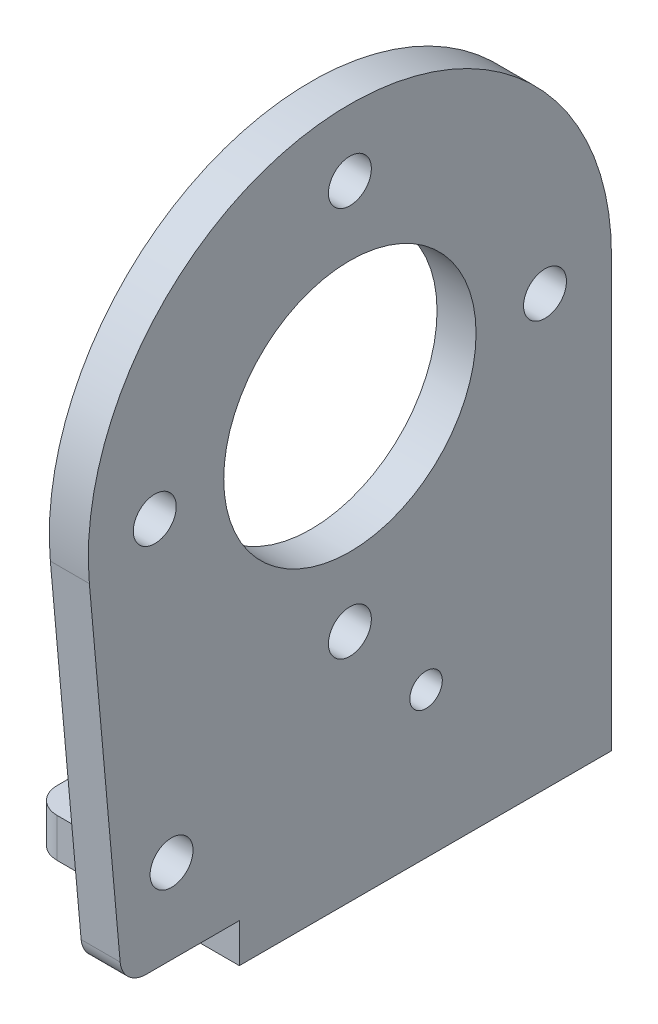
SolidWorks part; units mm, degrees
ref_plane "前视基准面" through (0, 0, 0) normal (0, 0, 1) x (1, 0, 0)
ref_plane "上视基准面" through (0, 0, 0) normal (0, 1, 0) x (1, 0, 0)
ref_plane "右视基准面" through (0, 0, 0) normal (1, 0, 0) x (0, 0, -1)
sketch "草图2" plane through (0, 0, 0) normal (1, 0, 0) x (0, 0, -1)
  line L0 (9, 13) -> (61, 13)
  line L1 (37.6103, 13) -> (37.6103, 10)
  line L2 (9, 10) -> (61, 10)
  line L5 (9, 10) -> (9, 16)
  line L6 (9, 16) -> (61, 16)
  line L7 (61, 10) -> (61, 16)
extrude "凸台-拉伸5" add sketch "草图2" against normal blind 16 contours L5 L2 L1 L0
sketch "草图5" plane through (0, 0, 0) normal (1, 0, 0) x (0, 0, -1)
  line L0 (37.6103, 42.9997) -> (37.6103, 57.801)
  line L1 (37.6103, 42.9997) -> (37.6103, 13)
  line L3 (0, 0) -> (0, 52.9088)
  line L4 (35.1701, 53.1122) -> (70.1701, 53.1122)
  line L9 (52.6701, 53.1122) -> (16.7421, 64.2983)
  line L10 (0, 13) -> (61, 13)
  line L15 (0, 13) -> (-3.2625, 49.3636)
  line L17 (70, 13) -> (61, 13)
  line L18 (52.6701, 53.1122) -> (61, 13)
  circle A0 centre (17.4998, 57.9997) radius 1.65
  circle A1 centre (32.4998, 42.9997) radius 1.65
  circle A2 centre (17.4998, 27.9997) radius 1.65
  circle A3 centre (2.4998, 42.9997) radius 1.65
  circle A6 centre (17.4998, 42.9997) radius 9.7
  circle A7 centre (17.4998, 42.9997) radius 20.1105
  circle A8 centre (48.125, 48) radius 1.65
  circle A9 centre (23.3549, 21.1974) radius 1.25
  circle A10 centre (53.0261, 18.2423) radius 1.65
  circle A11 centre (3.7886, 19.472) radius 1.65
  circle A12 centre (17.4998, 42.9997) radius 15
  point P16 (0, 0)
  point P21 (0, 0)
  point P23 (0, 0)
  point P37 (0, 0)
  dimension "D1" = 13
  dimension "D3" = 29.9997
  dimension "D4" = 17.4998
sketch "草图3" plane through (0, 13, 0) normal (0, 1, 0) x (1, 0, 0)
  line L0 (-16, 9) -> (0, 9) construction
  line L2 (-11.65, 22.35) -> (-11.65, 31.1)
  circle A0 centre (-11.65, 13.6) radius 1.65
  circle A1 centre (-11.65, 22.35) radius 1.65
  circle A2 centre (-11.65, 31.1) radius 1.65
  dimension "D1" = 4.6
  dimension "D2" = 8.75
extrude "切除-拉伸1" cut sketch "草图3" against normal blind 10
extrude "凸台-拉伸7" add sketch "草图5" against normal blind 3
fillet "圆角1" radius 2 3 edges at (-1.5, 13, 0) (-16, 11.5, -37.6103) (-16, 11.5, -9)
